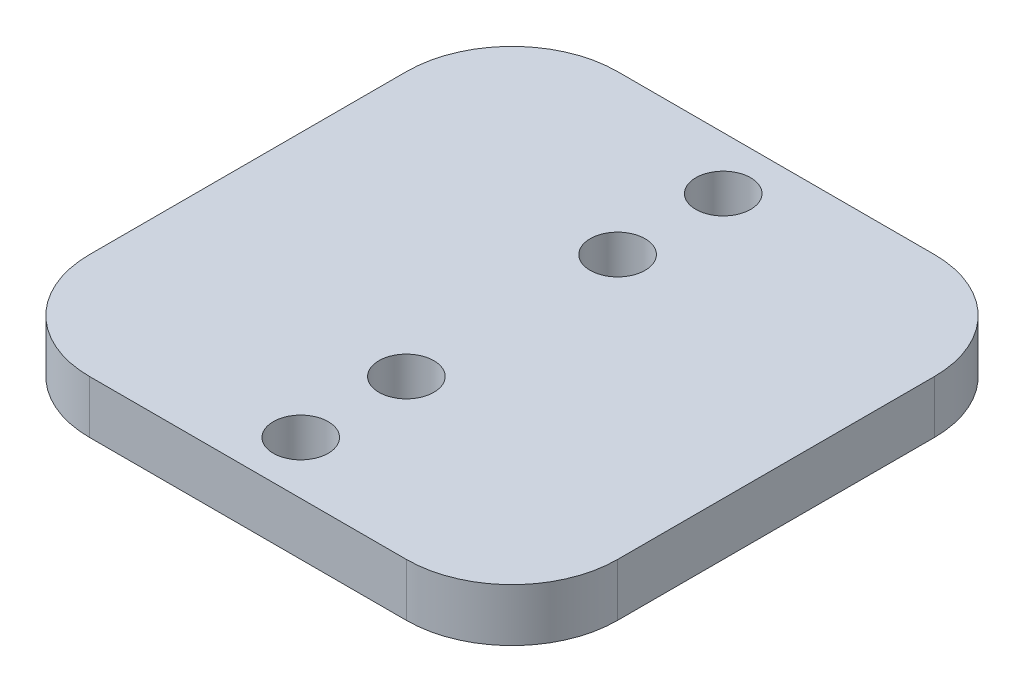
SolidWorks part; units mm, degrees
ref_plane "Front Plane" through (0, 0, 0) normal (0, 0, 1) x (1, 0, 0)
ref_plane "Top Plane" through (0, 0, 0) normal (0, 1, 0) x (1, 0, 0)
ref_plane "Right Plane" through (0, 0, 0) normal (1, 0, 0) x (0, 0, -1)
sketch "Sketch1" plane through (0, 0, 0) normal (0, 1, 0) x (1, 0, 0)
  line L1 (0, 0) -> (50, 0)
  line L2 (0, 0) -> (0, 50)
  line L3 (0, 50) -> (50, 50)
  line L4 (50, 0) -> (50, 50)
  dimension "D1" = 50
  dimension "D2" = 50
extrude "Boss-Extrude1" add sketch "Sketch1" along normal blind 5
sketch "Sketch2" plane through (0, 5, 0) normal (0, 1, 0) x (1, 0, 0)
  line L0 (0, 25) -> (50, 25) construction
  line L1 (0, 50) -> (0, 0) construction
  line L2 (50, 0) -> (50, 50) construction
  line L3 (25, 0) -> (25, 50) construction
  line L4 (0, 0) -> (50, 0) construction
  line L5 (50, 50) -> (0, 50) construction
  circle A0 centre (25, 35) radius 2.6
  circle A1 centre (25, 45) radius 2.6
  circle A2 centre (25, 15) radius 2.6
  circle A3 centre (25, 5) radius 2.6
  dimension "D1" = 5.2
  dimension "D2" = 5.2
  dimension "D3" = 10
  dimension "D4" = 20
extrude "Cut-Extrude1" cut sketch "Sketch2" against normal through all
fillet "Fillet1" radius 10 4 edges at (50, 2.5, 0) (0, 2.5, 0) (0, 2.5, -50) (50, 2.5, -50)
